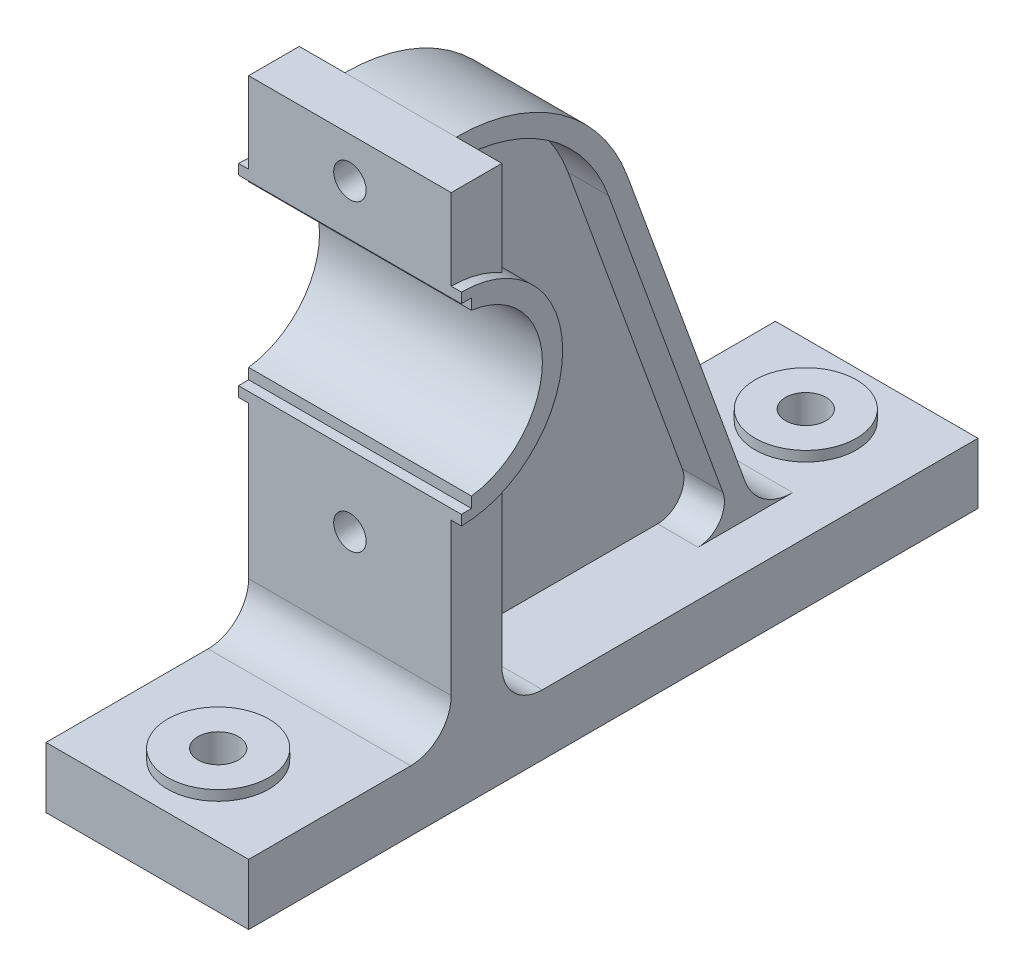
SolidWorks part; units mm, degrees
ref_plane "Front Plane" through (0, 0, 0) normal (0, 0, 1) x (1, 0, 0)
ref_plane "Top Plane" through (0, 0, 0) normal (0, 1, 0) x (1, 0, 0)
ref_plane "Right Plane" through (0, 0, 0) normal (1, 0, 0) x (0, 0, -1)
sketch "Sketch2" plane through (0, 0, 0) normal (1, 0, 0) x (0, 0, -1)
  line L0 (0, 0) -> (360, 0)
  line L1 (360, 0) -> (360, 30)
  line L2 (360, 30) -> (125, 30)
  line L3 (125, 30) -> (125, 265)
  line L4 (100, 265) -> (100, 30)
  line L5 (100, 30) -> (0, 30)
  line L6 (0, 30) -> (0, 0)
  line L7 (100, 265) -> (125, 265)
  dimension "D1" = 30
  dimension "D2" = 360
  dimension "D3" = 235
  dimension "D4" = 25
  dimension "D5" = 100
  dimension "D6" = 30
extrude "Boss-Extrude1" add sketch "Sketch2" along normal mid plane 100
sketch "Sketch7" plane through (0, 0, 0) normal (1, 0, 0) x (0, 0, -1)
  line L0 (100, 265) -> (100, 30) construction
  line L1 (100, 225) -> (100, 125)
  line L4 (125, 265) -> (100, 265) construction
  arc A0 (100, 225) -> (100, 125) centre (100, 175) cw
  dimension "D2" = 50
  dimension "D1" = 90
extrude "Boss-Extrude4" add sketch "Sketch7" along normal mid plane 110
sketch "Sketch11" plane through (0, 0, 0) normal (1, 0, 0) x (0, 0, -1)
  line L0 (209.5723, 205.7818) -> (273.5517, 30)
  line L1 (360, 30) -> (125, 30) construction
  line L2 (100, 175) -> (150, 175) construction
  line L4 (100, 225) -> (100, 125) construction
  line L5 (125, 265) -> (125, 30)
  line L6 (125, 30) -> (273.5517, 30)
  arc A0 (125, 265) -> (209.5723, 205.7818) centre (125, 175) cw
  arc A2 (100, 125) -> (100, 225) centre (100, 175) ccw construction
  dimension "D1" = 90
  dimension "D2" = 110
extrude "Boss-Extrude5" add sketch "Sketch11" along normal mid plane 55
sketch "Sketch12" plane through (27.5, 0, 0) normal (1, 0, 0) x (0, 0, -1)
  line L6 (125, 255) -> (125, 218.3013)
  line L7 (264.1548, 26.5798) -> (200.1754, 202.3616)
  line L8 (262.9099, 30) -> (200.1754, 202.3616)
  line L10 (125, 30) -> (273.5517, 30) construction
  line L11 (125, 30) -> (125, 131.6987) construction
  line L12 (125, 30) -> (262.9099, 30)
  line L13 (125, 30) -> (125, 131.6987)
  arc A7 (200.1754, 202.3616) -> (125, 255) centre (125, 175) ccw
  arc A8 (200.1754, 202.3616) -> (125, 255) centre (125, 175) ccw
  arc A9 (125, 131.6987) -> (125, 218.3013) centre (100, 175) ccw construction
  arc A10 (125, 131.6987) -> (125, 218.3013) centre (100, 175) ccw
  dimension "D1" = 10
extrude "Cut-Extrude1" cut sketch "Sketch12" against normal blind 20
mirror "Mirror1" about plane through (0, 0, 0) normal (1, 0, 0) of "Cut-Extrude1"
fillet "Fillet1" radius 13 2 edges at (-17.5, 30, -262.9099) (17.5, 30, -262.9099)
fillet "Fillet2" radius 25 1 edges at (0, 30, -273.5517)
fillet "Fillet3" radius 10 2 edges at (-17.5, 255, -125) (17.5, 255, -125)
fillet "Fillet4" radius 20 3 edges at (-28.75, 30, -125) (0, 30, -100) (28.75, 30, -125)
sketch "Sketch13" plane through (55, 0, 0) normal (1, 0, 0) x (0, 0, -1)
  line L0 (100, 225) -> (100, 125) construction
  line L1 (100, 215) -> (100, 135)
  arc A0 (100, 135) -> (100, 215) centre (100, 175) ccw
  dimension "D1" = 40
extrude "Cut-Extrude2" cut sketch "Sketch13" against normal through all both and the other way through all
sketch "Sketch14" plane through (55, 0, 0) normal (1, 0, 0) x (0, 0, -1)
  line L1 (105, 130) -> (95, 130)
  line L2 (105, 130) -> (105, 220)
  line L3 (105, 220) -> (95, 220)
  line L4 (95, 130) -> (95, 220)
  line L5 (105, 130) -> (95, 220) construction
  line L6 (105, 220) -> (95, 130) construction
  line L7 (100, 225) -> (100, 215) construction
  point P0 (100, 175)
  dimension "D1" = 5
  dimension "D2" = 5
extrude "Cut-Extrude3" cut sketch "Sketch14" against normal up to next and the other way through all
sketch "Sketch15" plane through (0, 30, 0) normal (0, 1, 0) x (1, 0, 0)
  line L0 (50, 0) -> (-50, 0) construction
  circle A0 centre (0, 35) radius 25
  dimension "D1" = 50
  dimension "D2" = 35
extrude "Boss-Extrude6" add sketch "Sketch15" along normal blind 5
pattern_linear "LPattern1" count 2 spacing 290 along (0, 0, -1) of "Boss-Extrude6"
hole_wizard "Hole1" positions "Sketch16" profile "Sketch17" legacy end condition through all
sketch "Sketch16" plane through (0, 35, 0) normal (0, 1, 0) x (1, 0, 0)
  point P0 (0, 35)
  point P3 (0, 325)
sketch "Sketch17" plane through (0, 35, -35) normal (1, 0, 0) x (0, 0, 1)
  line L0 (0, 0) -> (0, 35)
  line L1 (0, 35) -> (10, 35)
  line L2 (10, 35) -> (10, 0)
  line L3 (10, 0) -> (0, 0)
  line L4 (0, 110) -> (0, -10) construction
  dimension "Diameter" = 20
  dimension "Depth" = 35
hole_wizard "Hole2" positions "Sketch18" profile "Sketch19" legacy
sketch "Sketch18" plane through (0, 0, -100) normal (0, 0, 1) x (1, 0, 0)
  point P0 (0, 245)
  dimension "D1" = 245
sketch "Sketch19" plane through (0, 245, -100) normal (1, 0, 0) x (0, -1, 0)
  line L0 (0, 0) -> (0, 25)
  line L1 (0, 25) -> (8, 25)
  line L2 (8, 25) -> (8, 0)
  line L3 (8, 0) -> (0, 0)
  line L4 (0, 110) -> (0, -10) construction
  dimension "Diameter" = 16
  dimension "Depth" = 25
pattern_linear "LPattern2" count 2 spacing 150 along (0, -1, 0) of "Hole2"
